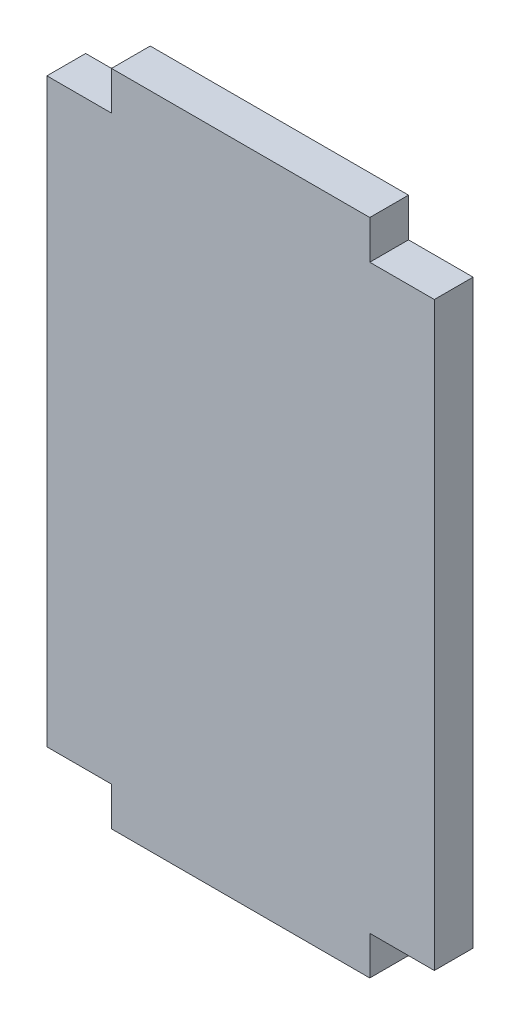
SolidWorks part; units mm, degrees
material "Maple"
ref_plane "Front Plane" through (0, 0, 0) normal (0, 0, 1) x (1, 0, 0)
ref_plane "Top Plane" through (0, 0, 0) normal (0, 1, 0) x (1, 0, 0)
ref_plane "Right Plane" through (0, 0, 0) normal (1, 0, 0) x (0, 0, -1)
sketch "Sketch1" plane through (0, 0, 0) normal (0, 0, 1) x (1, 0, 0)
  line L0 (-10, 25.5) -> (10, 25.5)
  line L1 (10, 25.5) -> (10, 22.5)
  line L2 (10, 22.5) -> (15, 22.5)
  line L3 (15, 22.5) -> (15, -22.5)
  line L4 (15, -22.5) -> (10, -22.5)
  line L5 (10, -22.5) -> (10, -25.5)
  line L6 (10, -25.5) -> (-10, -25.5)
  line L7 (-10, -25.5) -> (-10, -22.5)
  line L8 (-10, -22.5) -> (-15, -22.5)
  line L9 (-15, -22.5) -> (-15, 22.5)
  line L10 (-15, 22.5) -> (-10, 22.5)
  line L11 (-10, 22.5) -> (-10, 25.5)
  line L12 (-15, 0) -> (15, 0) construction
  point P15 (0, 0)
  dimension "D1" = 45
  dimension "D2" = 3
  dimension "D3" = 20
  dimension "D4" = 30
extrude "Boss-Extrude1" add sketch "Sketch1" along normal blind 3
